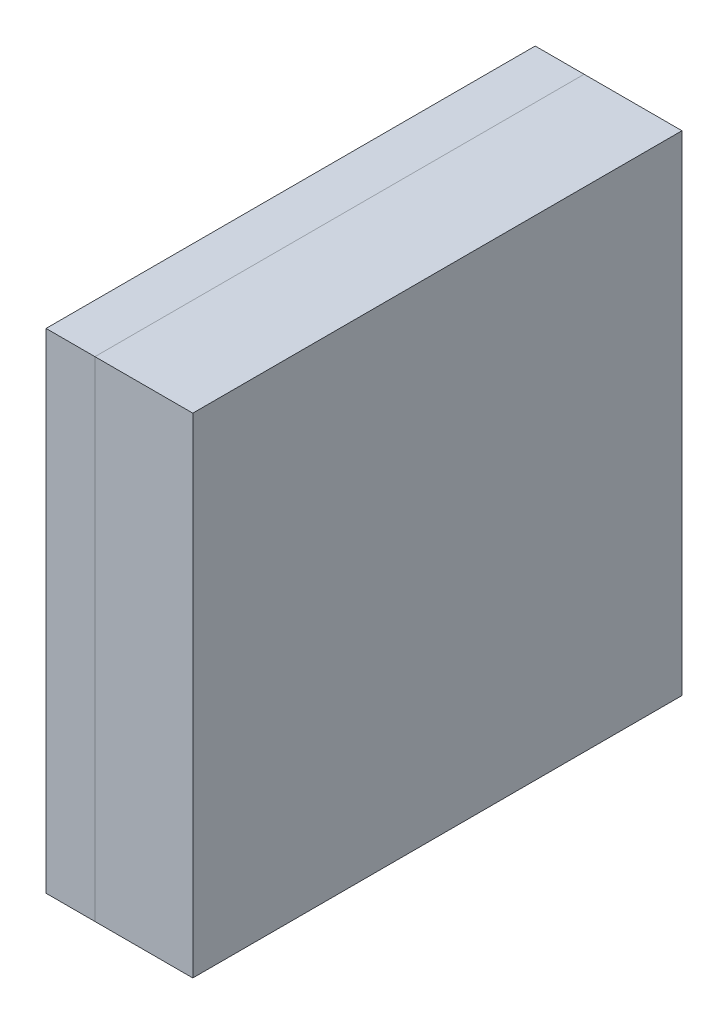
SolidWorks part; units mm, degrees
ref_plane "Front Plane" through (0, 0, 0) normal (0, 0, 1) x (1, 0, 0)
ref_plane "Top Plane" through (0, 0, 0) normal (0, 1, 0) x (1, 0, 0)
ref_plane "Right Plane" through (0, 0, 0) normal (1, 0, 0) x (0, 0, -1)
sketch "Sketch1" plane through (0, 0, 0) normal (1, 0, 0) x (0, 0, -1)
  line L1 (-500, -500) -> (500, -500)
  line L2 (-500, -500) -> (-500, 500)
  line L3 (-500, 500) -> (500, 500)
  line L4 (500, -500) -> (500, 500)
  line L5 (-500, -500) -> (500, 500) construction
  line L6 (-500, 500) -> (500, -500) construction
  point P0 (0, 0)
  dimension "D1" = 1000
  dimension "D2" = 1000
extrude "Boss-Extrude1" add sketch "Sketch1" along normal blind 100 contours L3 L4 L1 L2
sketch "Sketch2" plane through (100, 0, 0) normal (1, 0, 0) x (0, 0, -1)
  line L4 (-500, 500) -> (-500, -500)
  line L5 (-500, -500) -> (500, -500)
  line L6 (500, -500) -> (500, 500)
  line L7 (500, 500) -> (-500, 500)
  line L8 (-500, 500) -> (-500, -500)
  line L9 (-500, -500) -> (500, -500)
  line L10 (500, -500) -> (500, 500)
  line L11 (500, 500) -> (-500, 500)
  dimension "D2" = 1000
  dimension "D1" = 0
extrude "Boss-Extrude2" add sketch "Sketch2" along normal blind 200 separate body
